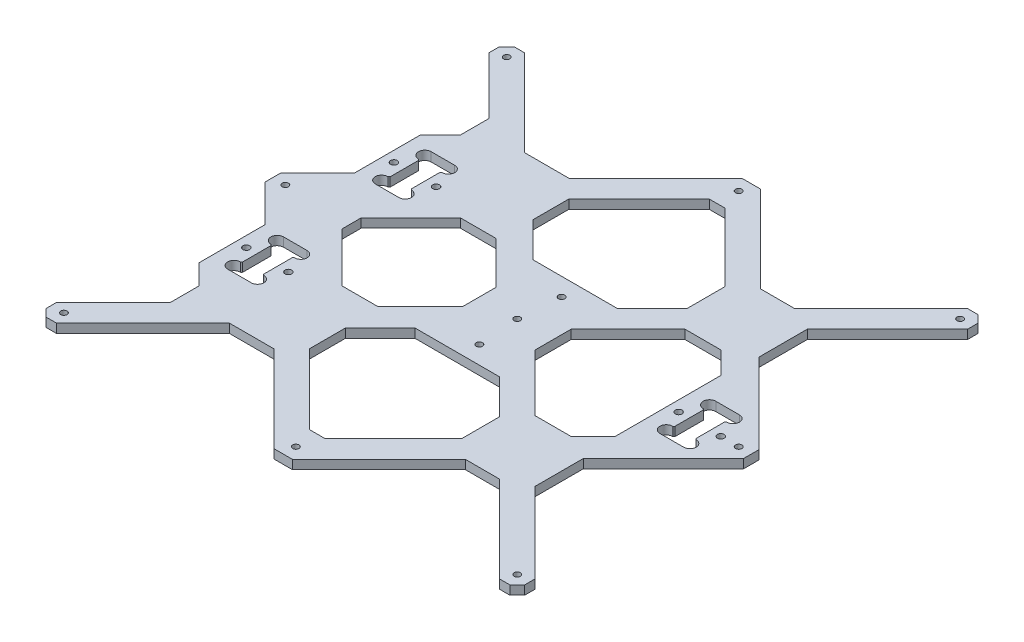
SolidWorks part; units mm, degrees
material "6063-O, Extruded Rod (SS)"
ref_plane "Front Plane" through (0, 0, 0) normal (0, 0, 1) x (1, 0, 0)
ref_plane "Top Plane" through (0, 0, 0) normal (0, 1, 0) x (1, 0, 0)
ref_plane "Right Plane" through (0, 0, 0) normal (1, 0, 0) x (0, 0, -1)
sketch "Sketch2" plane through (0, 0, 0) normal (0, 1, 0) x (1, 0, 0)
  line L0 (162, 177.023) -> (141.977, 157)
  line L1 (141.977, 157) -> (125, 157)
  line L2 (125, 157) -> (101.5, 180.5)
  line L3 (101.5, 189.5) -> (125, 213)
  line L4 (125, 213) -> (141.977, 213)
  line L5 (141.977, 213) -> (162, 192.977)
  line L6 (251.5, 210.0147) -> (240.9853, 220.5294)
  line L7 (240.9853, 220.5294) -> (224.0147, 220.5294)
  line L8 (224.0147, 220.5294) -> (197, 193.5147)
  line L9 (197, 176.4853) -> (224.0147, 149.4706)
  line L10 (224.0147, 149.4706) -> (240.9853, 149.4706)
  line L11 (240.9853, 149.4706) -> (251.5, 159.9853)
  line L12 (184.4001, 296) -> (225.4001, 255)
  line L13 (225.4001, 255) -> (241.5147, 255)
  line L14 (241.5147, 255) -> (282.5147, 296)
  line L15 (282.5147, 296) -> (287.4852, 296)
  line L16 (287.4852, 296) -> (291, 292.4852)
  line L17 (291, 292.4852) -> (291, 287.5147)
  line L18 (291, 287.5147) -> (253, 249.5147)
  line L19 (253, 249.5147) -> (253, 226.667)
  line L20 (253, 226.667) -> (291, 188.667)
  line L21 (291, 188.667) -> (291, 181.333)
  line L22 (291, 181.333) -> (253, 143.333)
  line L23 (253, 143.333) -> (253, 120.4853)
  line L24 (253, 120.4853) -> (291, 82.4853)
  line L25 (291, 82.4853) -> (291, 77.5148)
  line L26 (291, 77.5148) -> (287.4852, 74)
  line L27 (287.4852, 74) -> (282.5147, 74)
  line L28 (282.5147, 74) -> (241.5147, 115)
  line L29 (241.5147, 115) -> (225.4001, 115)
  line L30 (225.4001, 115) -> (184.4001, 74)
  line L31 (184.4001, 74) -> (175.5999, 74)
  line L32 (175.5999, 74) -> (134.5999, 115)
  line L33 (134.5999, 115) -> (113.4853, 115)
  line L34 (113.4853, 115) -> (72.4853, 74)
  line L35 (72.4853, 74) -> (67.5148, 74)
  line L36 (67.5148, 74) -> (64, 77.5148)
  line L37 (64, 77.5148) -> (64, 82.4853)
  line L38 (64, 82.4853) -> (91, 109.4853)
  line L39 (91, 109.4853) -> (91, 123)
  line L40 (91, 123) -> (81.5, 132.5)
  line L41 (81.5, 132.5) -> (81.5, 163.7609)
  line L42 (81.5, 163.7609) -> (64, 181.2609)
  line L43 (64, 188.7391) -> (81.5, 206.2391)
  line L44 (81.5, 206.2391) -> (81.5, 237.5)
  line L45 (81.5, 237.5) -> (91, 247)
  line L46 (91, 247) -> (91, 260.5147)
  line L47 (91, 260.5147) -> (64, 287.5147)
  line L48 (64, 287.5147) -> (64, 292.4852)
  line L49 (64, 292.4852) -> (67.5148, 296)
  line L50 (67.5148, 296) -> (72.4853, 296)
  line L51 (72.4853, 296) -> (113.4853, 255)
  line L52 (113.4853, 255) -> (134.5999, 255)
  line L53 (134.5999, 255) -> (175.5999, 296)
  line L54 (175.5999, 296) -> (184.4001, 296)
  line L55 (143, 246.4158) -> (143, 229.5663)
  line L56 (143, 229.5663) -> (159.5663, 213)
  line L57 (159.5663, 213) -> (199.5147, 213)
  line L58 (199.5147, 213) -> (216, 229.4853)
  line L59 (216, 229.4853) -> (216, 247.4296)
  line L60 (216, 247.4296) -> (183.6826, 279.747)
  line L61 (183.6826, 279.747) -> (176.3174, 279.7332)
  line L62 (176.3174, 279.7332) -> (143, 246.4158)
  line L63 (143, 123.5842) -> (143, 140.4337)
  line L64 (143, 140.4337) -> (159.5663, 157)
  line L65 (159.5663, 157) -> (199.5147, 157)
  line L66 (199.5147, 157) -> (216, 140.5147)
  line L67 (216, 140.5147) -> (216, 122.5704)
  line L68 (216, 122.5704) -> (183.6826, 90.253)
  line L69 (183.6826, 90.253) -> (176.3174, 90.2668)
  line L70 (176.3174, 90.2668) -> (143, 123.5842)
  line L71 (101.5, 226.75) -> (101.5, 213.25)
  line L72 (271.5, 191.75) -> (271.5, 178.25)
  line L73 (101.5, 156.75) -> (101.5, 143.25)
  line L74 (91.5, 226.75) -> (91.5, 213.25)
  line L75 (261.5, 191.75) -> (261.5, 178.25)
  line L76 (91.5, 156.75) -> (91.5, 143.25)
  line L77 (93.6792, 358.4107) -> (93.6792, 347.8262)
  line L78 (93.6792, 347.8262) -> (93.9406, 345.7354)
  line L79 (93.9406, 345.7354) -> (94.4633, 344.2327)
  line L80 (94.4633, 344.2327) -> (95.182, 343.1873)
  line L81 (95.182, 343.1873) -> (96.1846, 341.9648)
  line L82 (96.1846, 341.9648) -> (97.8105, 341.4329)
  line L83 (97.8105, 341.4329) -> (99.6248, 341.0966)
  line L84 (99.6248, 341.0966) -> (101.977, 341.3579)
  line L85 (101.977, 341.3579) -> (104.0024, 342.4033)
  line L86 (104.0024, 342.4033) -> (105.1131, 344.2327)
  line L87 (105.1131, 344.2327) -> (105.5705, 346.7155)
  line L88 (105.5705, 346.7155) -> (105.5705, 349.1983)
  line L89 (105.5705, 349.1983) -> (105.5705, 358.4107)
  line L90 (79.8932, 349.3289) -> (80.0892, 349.3289)
  line L91 (80.0892, 349.3289) -> (81.0039, 348.8063)
  line L92 (81.0039, 348.8063) -> (82.0493, 347.4342)
  line L93 (82.0493, 347.4342) -> (86.4922, 341.0966)
  line L94 (73.5556, 341.1619) -> (73.5556, 358.4107)
  line L95 (73.5556, 358.4107) -> (80.6119, 358.4107)
  line L96 (80.6119, 358.4107) -> (82.768, 357.7574)
  line L97 (82.768, 357.7574) -> (83.8134, 356.7773)
  line L98 (83.8134, 356.7773) -> (84.5321, 355.4706)
  line L99 (84.5321, 355.4706) -> (84.8588, 353.7065)
  line L100 (84.8588, 353.7065) -> (84.5321, 352.0078)
  line L101 (84.5321, 352.0078) -> (83.6827, 350.5703)
  line L102 (83.6827, 350.5703) -> (82.5067, 349.8517)
  line L103 (82.5067, 349.8517) -> (81.3306, 349.525)
  line L104 (81.3306, 349.525) -> (79.8932, 349.3289)
  line L105 (79.8932, 349.3289) -> (78.1291, 349.3289)
  line L106 (78.1291, 349.3289) -> (73.5556, 349.3289)
  line L107 (113.0897, 345.4442) -> (114.2004, 343.4842)
  line L108 (114.2004, 343.4842) -> (116.6178, 341.8507)
  line L109 (116.6178, 341.8507) -> (118.9699, 341.1974)
  line L110 (118.9699, 341.1974) -> (122.4328, 341.7201)
  line L111 (122.4328, 341.7201) -> (124.0662, 343.0268)
  line L112 (124.0662, 343.0268) -> (125.2422, 345.1176)
  line L113 (125.2422, 345.1176) -> (125.2422, 346.359)
  line L114 (125.2422, 346.359) -> (124.9156, 347.4697)
  line L115 (124.9156, 347.4697) -> (123.7395, 348.7764)
  line L116 (123.7395, 348.7764) -> (122.5635, 349.2991)
  line L117 (122.5635, 349.2991) -> (116.7485, 351.0632)
  line L118 (116.7485, 351.0632) -> (115.0497, 352.1739)
  line L119 (115.0497, 352.1739) -> (114.0044, 353.4153)
  line L120 (114.0044, 353.4153) -> (113.8737, 354.5914)
  line L121 (113.8737, 354.5914) -> (114.135, 356.3554)
  line L122 (114.135, 356.3554) -> (115.3764, 357.6622)
  line L123 (115.3764, 357.6622) -> (117.4672, 358.4462)
  line L124 (117.4672, 358.4462) -> (120.0807, 358.5769)
  line L125 (120.0807, 358.5769) -> (122.8248, 357.8582)
  line L126 (122.8248, 357.8582) -> (123.9355, 356.8128)
  line L127 (123.9355, 356.8128) -> (124.3929, 355.5714)
  line L128 (130.9954, 341.0312) -> (137.9864, 358.5414)
  line L129 (137.9864, 358.5414) -> (139.0972, 358.5414)
  line L130 (139.0972, 358.5414) -> (145.9575, 341.0312)
  line L131 (143.9343, 346.1951) -> (133.0803, 346.1927)
  line L132 (55, 341.1619) -> (55, 358.4107)
  line L133 (55, 358.4107) -> (62.0563, 358.4107)
  line L134 (62.0563, 358.4107) -> (64.2125, 357.7574)
  line L135 (64.2125, 357.7574) -> (65.2578, 356.7773)
  line L136 (65.2578, 356.7773) -> (65.9765, 355.4706)
  line L137 (65.9765, 355.4706) -> (66.3032, 353.7065)
  line L138 (66.3032, 353.7065) -> (65.9765, 352.0078)
  line L139 (65.9765, 352.0078) -> (65.1272, 350.5703)
  line L140 (65.1272, 350.5703) -> (63.9511, 349.8517)
  line L141 (63.9511, 349.8517) -> (62.7751, 349.525)
  line L142 (62.7751, 349.525) -> (61.3376, 349.3289)
  line L143 (61.3376, 349.3289) -> (59.5735, 349.3289)
  line L144 (59.5735, 349.3289) -> (55, 349.3289)
  line L145 (251.5, 210.0147) -> (251.5, 159.9853)
  line L146 (197, 193.5147) -> (197, 176.4853)
  line L147 (64, 188.7391) -> (64, 181.2609)
  line L148 (101.5, 189.5) -> (101.5, 180.5)
  line L149 (162, 192.977) -> (162, 177.023)
  line L150 (102.1, 142.75) -> (102, 142.75)
  line L151 (272.1, 177.75) -> (272, 177.75)
  line L152 (102.1, 212.75) -> (102, 212.75)
  line L153 (90.9, 142.75) -> (91, 142.75)
  line L154 (260.9, 177.75) -> (261, 177.75)
  line L155 (90.9, 212.75) -> (91, 212.75)
  line L156 (102, 142.75) -> (101.5, 143.25)
  line L157 (272, 177.75) -> (271.5, 178.25)
  line L158 (102, 212.75) -> (101.5, 213.25)
  line L159 (91, 142.75) -> (91.5, 143.25)
  line L160 (261, 177.75) -> (261.5, 178.25)
  line L161 (91, 212.75) -> (91.5, 213.25)
  line L162 (102.1, 157.25) -> (102, 157.25)
  line L163 (272.1, 192.25) -> (272, 192.25)
  line L164 (102.1, 227.25) -> (102, 227.25)
  line L165 (90.9, 157.25) -> (91, 157.25)
  line L166 (260.9, 192.25) -> (261, 192.25)
  line L167 (90.9, 227.25) -> (91, 227.25)
  line L168 (101.5, 156.75) -> (102, 157.25)
  line L169 (271.5, 191.75) -> (272, 192.25)
  line L170 (101.5, 226.75) -> (102, 227.25)
  line L171 (91.5, 156.75) -> (91, 157.25)
  line L172 (261.5, 191.75) -> (261, 192.25)
  line L173 (91.5, 226.75) -> (91, 227.25)
  line L174 (90.9, 163.25) -> (102.1, 163.25)
  line L175 (260.9, 198.25) -> (272.1, 198.25)
  line L176 (90.9, 233.25) -> (102.1, 233.25)
  line L177 (90.9, 136.75) -> (102.1, 136.75)
  line L178 (260.9, 171.75) -> (272.1, 171.75)
  line L179 (90.9, 206.75) -> (102.1, 206.75)
  arc A0 (102.1, 206.75) -> (102.1, 212.75) centre (102.1, 209.75) ccw
  arc A1 (272.1, 171.75) -> (272.1, 177.75) centre (272.1, 174.75) ccw
  arc A2 (102.1, 136.75) -> (102.1, 142.75) centre (102.1, 139.75) ccw
  arc A3 (90.9, 142.75) -> (90.9, 136.75) centre (90.9, 139.75) ccw
  arc A4 (90.9, 212.75) -> (90.9, 206.75) centre (90.9, 209.75) ccw
  arc A5 (260.9, 177.75) -> (260.9, 171.75) centre (260.9, 174.75) ccw
  arc A6 (102.1, 157.25) -> (102.1, 163.25) centre (102.1, 160.25) ccw
  arc A7 (102.1, 227.25) -> (102.1, 233.25) centre (102.1, 230.25) ccw
  arc A8 (272.1, 192.25) -> (272.1, 198.25) centre (272.1, 195.25) ccw
  arc A9 (90.9, 163.25) -> (90.9, 157.25) centre (90.9, 160.25) ccw
  arc A10 (260.9, 198.25) -> (260.9, 192.25) centre (260.9, 195.25) ccw
  arc A11 (90.9, 233.25) -> (90.9, 227.25) centre (90.9, 230.25) ccw
  circle A12 centre (318.6, 4.9) radius 2.55
  circle A13 centre (318.6, 28.1) radius 2.55
  circle A14 centre (295.4, 28.1) radius 2.55
  circle A15 centre (295.4, 4.9) radius 2.55
  circle A16 centre (281.6, 4.9) radius 2.55
  circle A17 centre (258.4, 4.9) radius 2.55
  circle A18 centre (258.4, 28.1) radius 2.55
  circle A19 centre (281.6, 28.1) radius 2.55
  circle A20 centre (111.6, 4.9) radius 2.55
  circle A21 centre (111.6, 28.1) radius 2.55
  circle A22 centre (88.4, 28.1) radius 2.55
  circle A23 centre (88.4, 4.9) radius 2.55
  circle A24 centre (74.6, 4.9) radius 2.55
  circle A25 centre (74.6, 28.1) radius 2.55
  circle A26 centre (51.4, 28.1) radius 2.55
  circle A27 centre (51.4, 4.9) radius 2.55
  circle A28 centre (360, 39.8) radius 1.5
  circle A29 centre (10, 39.8) radius 1.5
  circle A30 centre (340, 359.8) radius 1.5
  circle A31 centre (30, 39.8) radius 1.5
  circle A32 centre (42.9, 67.8) radius 1.5
  circle A33 centre (340, 39.8) radius 1.5
  circle A34 centre (10, 359.8) radius 1.5
  circle A35 centre (350, 19.8) radius 1.5
  circle A36 centre (47, 99.8) radius 1.5
  circle A37 centre (3.7, 181.1) radius 1.5
  circle A38 centre (20, 19.8) radius 1.5
  circle A39 centre (4.9, 67.8) radius 1.5
  circle A40 centre (360, 359.8) radius 1.5
  circle A41 centre (42.9, 161.8) radius 1.5
  circle A42 centre (3.7, 99.8) radius 1.5
  circle A43 centre (30, 359.8) radius 1.5
  circle A44 centre (47, 174.7) radius 1.5
  circle A45 centre (4.9, 161.8) radius 1.5
  circle A46 centre (46.5, 269.3) radius 1.5
  circle A47 centre (15, 247.8) radius 1.5
  circle A48 centre (3.5, 269.3) radius 1.5
  circle A49 centre (15, 290.8) radius 1.5
  circle A50 centre (180, 80) radius 1.5
  circle A51 centre (180, 290) radius 1.5
  circle A52 centre (285, 80) radius 1.5
  circle A53 centre (70, 290) radius 1.5
  circle A54 centre (285, 290) radius 1.5
  circle A55 centre (70, 185) radius 1.5
  circle A56 centre (180, 185) radius 1.5
  circle A57 centre (285, 185) radius 1.5
  circle A58 centre (256.5, 185) radius 1.6
  circle A59 centre (276.5, 185) radius 1.6
  circle A60 centre (106.5, 220) radius 1.6
  circle A61 centre (106.5, 150) radius 1.6
  circle A62 centre (86.5, 220) radius 1.6
  circle A63 centre (86.5, 150) radius 1.6
  circle A64 centre (70, 80) radius 1.5
  circle A65 centre (181.5, 165.5) radius 1.5
  circle A66 centre (181.5, 204.5) radius 1.5
  circle A67 centre (40, 7) radius 1.6
  circle A68 centre (331, 7) radius 1.6
  circle A69 centre (343, 7) radius 1.6
  circle A70 centre (120, 13) radius 1.6
  circle A71 centre (120, 4) radius 1.6
  circle A72 centre (230, 13) radius 1.6
  circle A73 centre (230, 4) radius 1.6
  circle A74 centre (333.4, 205) radius 2.1
  circle A75 centre (333.4, 88) radius 2.1
  circle A76 centre (26, 7) radius 1.6
  circle A77 centre (153, 13) radius 1.6
  circle A78 centre (153, 4) radius 1.6
  spline S0 degree 2 poles (5, 370) (2.5, 367.5) (0, 365) knots 1472.868668 1472.868668 1472.868668 1479.939736 1479.939736 1479.939736
  spline S1 degree 2 poles (365, 370) (185, 370) (5, 370) knots 1112.868668 1112.868668 1112.868668 1472.868668 1472.868668 1472.868668
  spline S2 degree 2 poles (370, 365) (367.5, 367.5) (365, 370) knots 1105.7976 1105.7976 1105.7976 1112.868668 1112.868668 1112.868668
  spline S3 degree 2 poles (370, 5) (370, 185) (370, 365) knots 745.7976 745.7976 745.7976 1105.7976 1105.7976 1105.7976
  spline S4 degree 2 poles (365, 0) (367.5, 2.5) (370, 5) knots 738.726533 738.726533 738.726533 745.7976 745.7976 745.7976
  spline S5 degree 2 poles (345, 0) (355, 0) (365, 0) knots 718.726533 718.726533 718.726533 738.726533 738.726533 738.726533
  spline S6 degree 2 poles (341, 4) (343, 2) (345, 0) knots 710.241251 710.241251 710.241251 718.726533 718.726533 718.726533
  spline S7 degree 2 poles (333, 4) (337, 4) (341, 4) knots 704.241251 704.241251 704.241251 710.241251 710.241251 710.241251
  spline S8 degree 2 poles (329, 0) (331, 2) (333, 4) knots 698.584397 698.584397 698.584397 704.241251 704.241251 704.241251
  spline S9 degree 2 poles (151, 0) (240, 0) (329, 0) knots 507.584397 507.584397 507.584397 698.584397 698.584397 698.584397
  spline S10 degree 2 poles (146, 5) (148.5, 2.5) (151, 0) knots 501.927543 501.927543 501.927543 507.584397 507.584397 507.584397
  spline S11 degree 2 poles (127, 5) (136.5, 5) (146, 5) knots 487.927543 487.927543 487.927543 501.927543 501.927543 501.927543
  spline S12 degree 2 poles (122, 0) (124.5, 2.5) (127, 5) knots 482.270688 482.270688 482.270688 487.927543 487.927543 487.927543
  spline S13 degree 2 poles (41, 0) (81.5, 0) (122, 0) knots 407.270688 407.270688 407.270688 482.270688 482.270688 482.270688
  spline S14 degree 2 poles (37, 4) (39, 2) (41, 0) knots 401.613834 401.613834 401.613834 407.270688 407.270688 407.270688
  spline S15 degree 2 poles (29, 4) (33, 4) (37, 4) knots 395.613834 395.613834 395.613834 401.613834 401.613834 401.613834
  spline S16 degree 2 poles (25, 0) (27, 2) (29, 4) knots 387.128553 387.128553 387.128553 395.613834 395.613834 395.613834
  spline S17 degree 2 poles (5, 0) (15, 0) (25, 0) knots 367.128553 367.128553 367.128553 387.128553 387.128553 387.128553
  spline S18 degree 2 poles (0, 5) (2.5, 2.5) (5, 0) knots 360.191742 360.191742 360.191742 367.128553 367.128553 367.128553
  spline S19 degree 2 poles (0, 365) (0, 185) (0, 5) knots 0 0 0 360.191742 360.191742 360.191742
  spline S20 degree 2 poles (93, 31.5) (100, 31.5) (107, 31.5) knots 1110.421356 1110.421356 1110.421356 1117.046356 1117.046356 1117.046356
  spline S21 degree 2 poles (88, 36.5) (90.5, 34) (93, 31.5) knots 1103.350288 1103.350288 1103.350288 1110.421356 1110.421356 1110.421356
  spline S22 degree 2 poles (83, 36.5) (85.5, 36.5) (88, 36.5) knots 1098.350288 1098.350288 1098.350288 1103.350288 1103.350288 1103.350288
  spline S23 degree 2 poles (73, 46.5) (78, 41.5) (83, 36.5) knots 1084.208153 1084.208153 1084.208153 1098.350288 1098.350288 1098.350288
  spline S24 degree 2 poles (55, 46.5) (64, 46.5) (73, 46.5) knots 1066.208153 1066.208153 1066.208153 1084.208153 1084.208153 1084.208153
  spline S25 degree 2 poles (50, 51.5) (52.5, 49) (55, 46.5) knots 1059.137085 1059.137085 1059.137085 1066.208153 1066.208153 1066.208153
  spline S26 degree 2 poles (50, 325) (50, 188.25) (50, 51.5) knots 787.637085 787.637085 787.637085 1059.137085 1059.137085 1059.137085
  spline S27 degree 2 poles (55, 330) (52.5, 327.5) (50, 325) knots 780.566017 780.566017 780.566017 787.637085 787.637085 787.637085
  spline S28 degree 2 poles (315, 330) (185, 330) (55, 330) knots 520.566017 520.566017 520.566017 780.566017 780.566017 780.566017
  spline S29 degree 2 poles (320, 325) (317.5, 327.5) (315, 330) knots 513.494949 513.494949 513.494949 520.566017 520.566017 520.566017
  spline S30 degree 2 poles (320, 51.5) (320, 188.25) (320, 325) knots 241.994949 241.994949 241.994949 513.494949 513.494949 513.494949
  spline S31 degree 2 poles (315, 46.5) (317.5, 49) (320, 51.5) knots 234.923882 234.923882 234.923882 241.994949 241.994949 241.994949
  spline S32 degree 2 poles (297, 46.5) (306, 46.5) (315, 46.5) knots 216.923882 216.923882 216.923882 234.923882 234.923882 234.923882
  spline S33 degree 2 poles (287, 36.5) (292, 41.5) (297, 46.5) knots 202.781746 202.781746 202.781746 216.923882 216.923882 216.923882
  spline S34 degree 2 poles (282, 36.5) (284.5, 36.5) (287, 36.5) knots 197.781746 197.781746 197.781746 202.781746 202.781746 202.781746
  spline S35 degree 2 poles (277, 31.5) (279.5, 34) (282, 36.5) knots 190.710678 190.710678 190.710678 197.781746 197.781746 197.781746
  spline S36 degree 2 poles (263, 31.5) (264, 31.5) (265, 31.5) (270, 31.5) (275, 31.5) (276, 31.5) (277, 31.5) knots 176.710678 176.710678 176.710678 178.710678 178.710678 188.710678 188.710678 190.710678 190.710678 190.710678
  spline S37 degree 2 poles (258, 36.5) (260.5, 34) (263, 31.5) knots 169.63961 169.63961 169.63961 176.710678 176.710678 176.710678
  spline S38 degree 2 poles (210, 36.5) (211.75, 36.5) (213.5, 36.5) (235.75, 36.5) (258, 36.5) knots 121.63961 121.63961 121.63961 125.13961 125.13961 169.63961 169.63961 169.63961
  spline S39 degree 2 poles (190, 16.5) (200, 26.5) (210, 36.5) knots 93.355339 93.355339 93.355339 121.63961 121.63961 121.63961
  spline S40 degree 2 poles (180, 16.5) (185, 16.5) (190, 16.5) knots 83.355339 83.355339 83.355339 93.355339 93.355339 93.355339
  spline S41 degree 2 poles (160, 36.5) (170, 26.5) (180, 16.5) knots 55.071068 55.071068 55.071068 83.355339 83.355339 83.355339
  spline S42 degree 2 poles (112, 36.5) (134.25, 36.5) (156.5, 36.5) (158.25, 36.5) (160, 36.5) knots 7.071068 7.071068 7.071068 51.571068 51.571068 55.071068 55.071068 55.071068
  spline S43 degree 2 poles (107, 31.5) (109.5, 34) (112, 36.5) knots 0 0 0 7.071068 7.071068 7.071068
extrude "Boss-Extrude2" add sketch "Sketch2" along normal blind 4.25 contours L43 L147 L42 L41 L40 L39 L38 L37 L36 L35 L34 L33 L32 L31 L30 L29 L28 L27 L26 L25 L24 L23 L22 L21 L20 L19 L18 L17 L16 L15 L14 L13 L12 L54 L53 L52 L51 L50 L49 L48 L47 L46 L45 L44 A66 A65 A64
sketch "Sketch3" plane through (0, 4.25, 0) normal (0, 1, 0) x (1, 0, 0)
  line L0 (181.5, 203) -> (181.5, 206) construction
  line L1 (180, 204.5) -> (183, 204.5) construction
  line L2 (180, 165.5) -> (183, 165.5) construction
  circle A0 centre (181.5, 204.5) radius 1.5 construction
  circle A1 centre (181.5, 204.5) radius 1.5 construction
  circle A2 centre (181.5, 165.5) radius 1.5 construction
ref_plane "Plane1" through (181.5, 0, 0) normal (1, 0, 0) x (0, 0, -1)
ref_plane "Plane2" through (0, 0, -165.5) normal (0, 0, 1) x (1, 0, 0)
ref_plane "Plane3" through (0, 0, -204.5) normal (0, 0, -1) x (-1, 0, 0)
